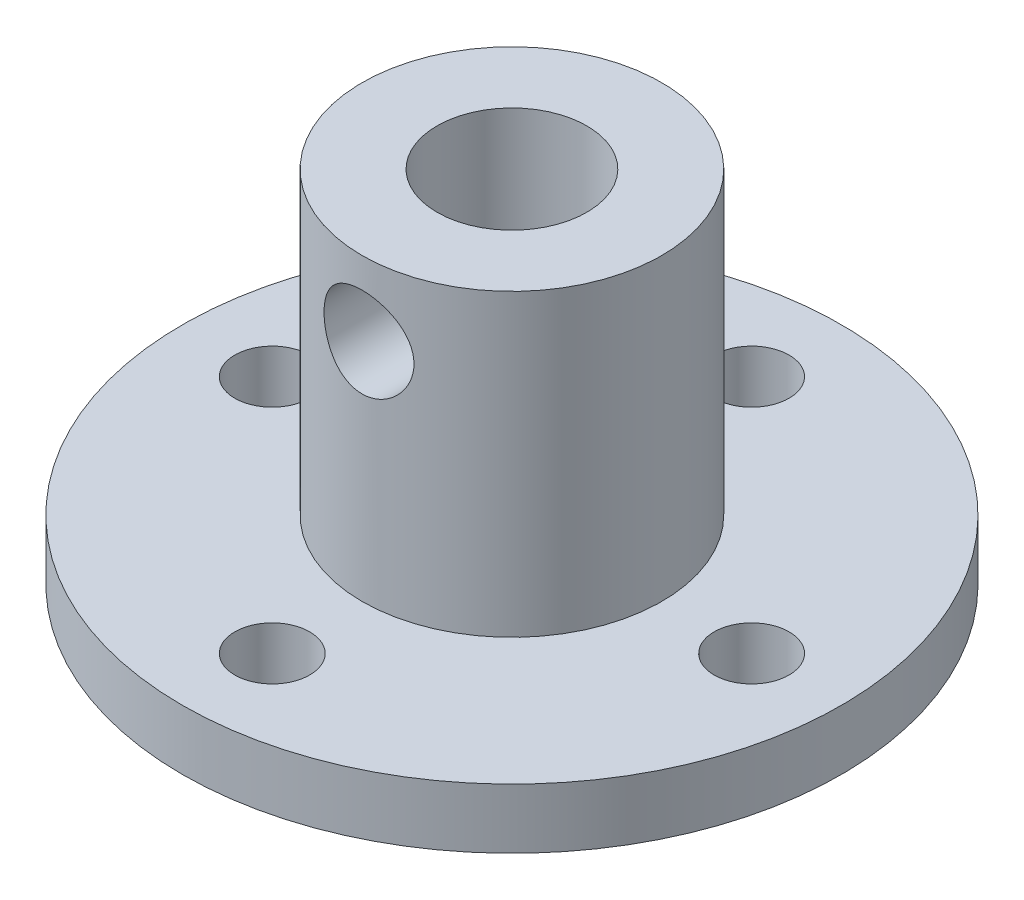
SolidWorks part; units mm, degrees
ref_plane "前基準面" through (0, 0, 0) normal (0, 0, 1) x (1, 0, 0)
ref_plane "上基準面" through (0, 0, 0) normal (0, 1, 0) x (1, 0, 0)
ref_plane "右基準面" through (0, 0, 0) normal (1, 0, 0) x (0, 0, -1)
sketch "草圖1" plane through (0, 0, 0) normal (0, 1, 0) x (1, 0, 0)
  line L0 (0, 0) -> (0, 8) construction
  line L1 (0, 0) -> (8, 0) construction
  line L2 (0, 0) -> (0, -8) construction
  line L3 (0, 0) -> (-8, 0) construction
  circle A0 centre (0, 0) radius 11
  circle A1 centre (0, 8) radius 1.25
  circle A2 centre (8, 0) radius 1.25
  circle A3 centre (0, -8) radius 1.25
  circle A4 centre (-8, 0) radius 1.25
  point P14 (0, 0)
  dimension "D1" = 22
  dimension "D3" = 2.5
  dimension "D2" = 8
  dimension "D4" = 4
extrude "填料-伸長1" add sketch "草圖1" along normal blind 2
sketch "草圖2" plane through (0, 2, 0) normal (0, 1, 0) x (1, 0, 0)
  circle A0 centre (0, 0) radius 5
  circle A1 centre (0, 0) radius 2.5
  dimension "D1" = 10
  dimension "D2" = 5
extrude "填料-伸長2" add sketch "草圖2" along normal blind 10
sketch "草圖3" plane through (0, 0, 0) normal (0, 0, 1) x (1, 0, 0)
  line L0 (0, 13.1643) -> (0, -0.9047) construction
  line L1 (5, 12) -> (-5, 12) construction
  circle A0 centre (0, 9.5) radius 1.5
  dimension "D1" = 3
  dimension "D2" = 2.5
extrude "除料-伸長1" cut sketch "草圖3" along normal up to next
